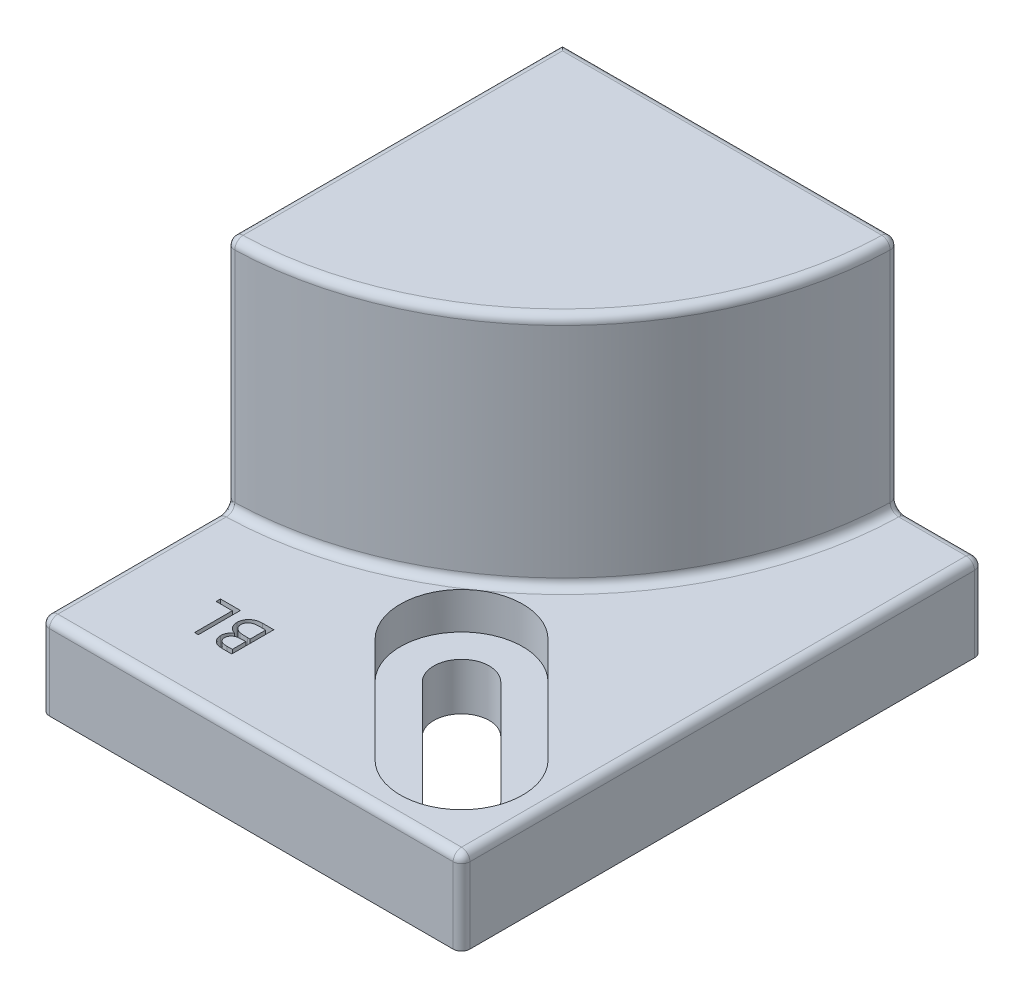
SolidWorks part; units mm, degrees
other "Markup1"
sketch "Sketch1" plane through (0, 0, 0) normal (0.5774, 0.5773, 0.5774) x (0.7071, 0, -0.7071)
sketch "Sketch2" plane through (0, 0, 0) normal (0.5774, 0.5773, 0.5774) x (0.7071, 0, -0.7071)
ref_plane "Front (z)" through (0, 0, 0) normal (0, 0, 1) x (1, 0, 0)
ref_plane "Top (y)" through (0, 0, 0) normal (0, 1, 0) x (1, 0, 0)
ref_plane "Right (x)" through (0, 0, 0) normal (1, 0, 0) x (0, 0, -1)
sketch "Sketch3" plane through (0, 0, 0) normal (0, 1, 0) x (1, 0, 0)
  line L1 (-25, -31) -> (25, -31)
  line L2 (-25, -31) -> (-25, 31)
  line L3 (-25, 31) -> (25, 31)
  line L4 (25, -31) -> (25, 31)
  line L5 (-25, -31) -> (25, 31) construction
  line L6 (-25, 31) -> (25, -31) construction
  point P0 (0, 0)
  dimension "D1" = 50
  dimension "D2" = 62
extrude "Boss-Extrude1" add sketch "Sketch3" along normal blind 10
hole_wizard "CBORE for M6 Hex Head Bolt1" positions "Sketch4" profile "Sketch5" counterbore size "M6" standard "ANSI Metric" end condition through all
sketch "Sketch4" plane through (0, 10, 0) normal (0, 1, 0) x (1, 0, 0)
  line L0 (-25, -31) -> (25, -31) construction
  line L1 (25, -31) -> (25, 31) construction
  point P0 (15, -21)
  dimension "D1" = 10
  dimension "D2" = 10
sketch "Sketch5" plane through (15, 10, 21) normal (1, 0, 0) x (0, 0, 1)
  line L0 (0, 0) -> (0, 10)
  line L1 (0, 10) -> (3.3, 10)
  line L3 (3.3, 10) -> (3.3, 4.38)
  line L4 (3.3, 4.38) -> (7.275, 4.38)
  line L5 (7.275, 4.38) -> (7.275, 0)
  line L7 (7.275, 0) -> (0, 0)
  line L11 (0, -6.35) -> (0, 107.95) construction
  dimension "Thru Hole Dia." = 6.6
  dimension "Thru Hole Depth" = 10
  dimension "C'Bore Dia." = 14.55
  dimension "C'Bore Depth" = 4.38
sketch "Sketch8" plane through (0, 10, 0) normal (0, 1, 0) x (1, 0, 0)
  line L0 (15, 31) -> (5, 31)
  line L1 (-25, 1) -> (-25, -9)
  arc A0 (-25, 1) -> (5, 31) centre (-25, 31) ccw
  arc A1 (-25, -9) -> (15, 31) centre (-25, 31) ccw
  circle A3 centre (-25, 31) radius 40 construction
  circle A4 centre (-25, 31) radius 30 construction
  point P4 (3.6891, 33.7712)
  point P9 (-5, 25)
  dimension "D1" = 60
  dimension "D3" = 62
  dimension "D4" = 50
  dimension "D2" = 10
extrude "Boss-Extrude3" add sketch "Sketch8" along normal blind 18
sketch "Sketch9" plane through (0, 28, 0) normal (0, 1, 0) x (1, 0, 0)
  line L0 (15, 31) -> (-25, 31)
  line L1 (-25, 31) -> (-25, -9)
  arc A0 (-25, -9) -> (15, 31) centre (-25, 31) ccw construction
  arc A1 (-25, -9) -> (15, 31) centre (-25, 31) ccw
extrude "Boss-Extrude4" add sketch "Sketch9" along normal blind 10
sketch "Sketch10" plane through (0, 10, 0) normal (0, 1, 0) x (1, 0, 0)
  line L2 (15, 31) -> (-25, 31) construction
  line L3 (-25, 31) -> (-25, -9) construction
  circle A0 centre (-12.5, 18.5) radius 3
  dimension "D1" = 6
  dimension "D2" = 12.5
  dimension "D3" = 12.5
extrude "Cut-Extrude2" cut sketch "Sketch10" against normal blind 6
fillet "Fillet1" radius 1 21 edges at (-10, 28, -31) (-10, 10, -31) (-25, 28, -16) (-25, 10, -16) (15, 24, -31) (-25, 24, 9) (5, 19, -31) (-3.7868, 28, -9.7868) (-25, 19, -1) (-3.7868, 10, -9.7868) (-25, 38, -11) (3.2843, 38, -2.7157) (-5, 38, -31) (20, 10, -31) (25, 5, -31) (25, 10, 0) (25, 5, 31) (-25, 5, 31) (0, 10, 31) (-25, 10, 20) (3.2843, 10, -2.7157)
sketch "Sketch12" plane through (0, 10, 0) normal (0, 1, 0) x (1, 0, 0)
  line L0 (-24, 30) -> (2.5772, 3.4228) construction
  line L1 (15, -21) -> (-20.9877, 14.9877) construction
  line L3 (9.8558, -26.1442) -> (-2.5401, -13.7483)
  line L4 (20.1442, -15.8558) -> (7.7483, -3.4599)
  line L7 (-24, 30) -> (-25, 31) construction
  arc A1 (9.8558, -26.1442) -> (20.1442, -15.8558) centre (15, -21) ccw
  arc A2 (7.7483, -3.4599) -> (-2.5401, -13.7483) centre (2.6041, -8.6041) ccw
  circle A3 centre (15, -21) radius 7.275 construction
  circle A5 centre (15, -21) radius 7.275 construction
  arc A6 (-24, -9.9878) -> (15.9878, 30) centre (-25, 31) ccw construction
  arc A8 (-24, -7.9872) -> (13.9872, 30) centre (-25, 31) ccw construction
extrude "Cut-Extrude3" cut sketch "Sketch12" against normal up to surface (4.38 mm away) up to face at (15, 5.62, 24.3)
sketch "Sketch13" plane through (0, 5.62, 0) normal (0, 1, 0) x (1, 0, 0)
  line L0 (-2.5401, -13.7483) -> (7.7483, -3.4599) construction
  line L1 (0.2707, -10.9376) -> (12.6665, -23.3335)
  line L2 (4.9376, -6.2707) -> (17.3335, -18.6665)
  arc A0 (4.9376, -6.2707) -> (0.2707, -10.9376) centre (2.6041, -8.6041) ccw
  circle A1 centre (15, -21) radius 3.3 construction
  arc A3 (12.6665, -23.3335) -> (17.3335, -18.6665) centre (15, -21) ccw
extrude "Cut-Extrude4" cut sketch "Sketch13" against normal through all
sketch "Sketch14" plane through (0, 10, 0) normal (0, 1, 0) x (1, 0, 0)
  line L0 (0, -18.771) -> (-25, -18.771) construction
  line L1 (-25, -30) -> (-25, -9.9878) construction
  text T0 "BL" font "Century Gothic" height 5
extrude "Cut-Extrude5" cut sketch "Sketch14" against normal blind 2
